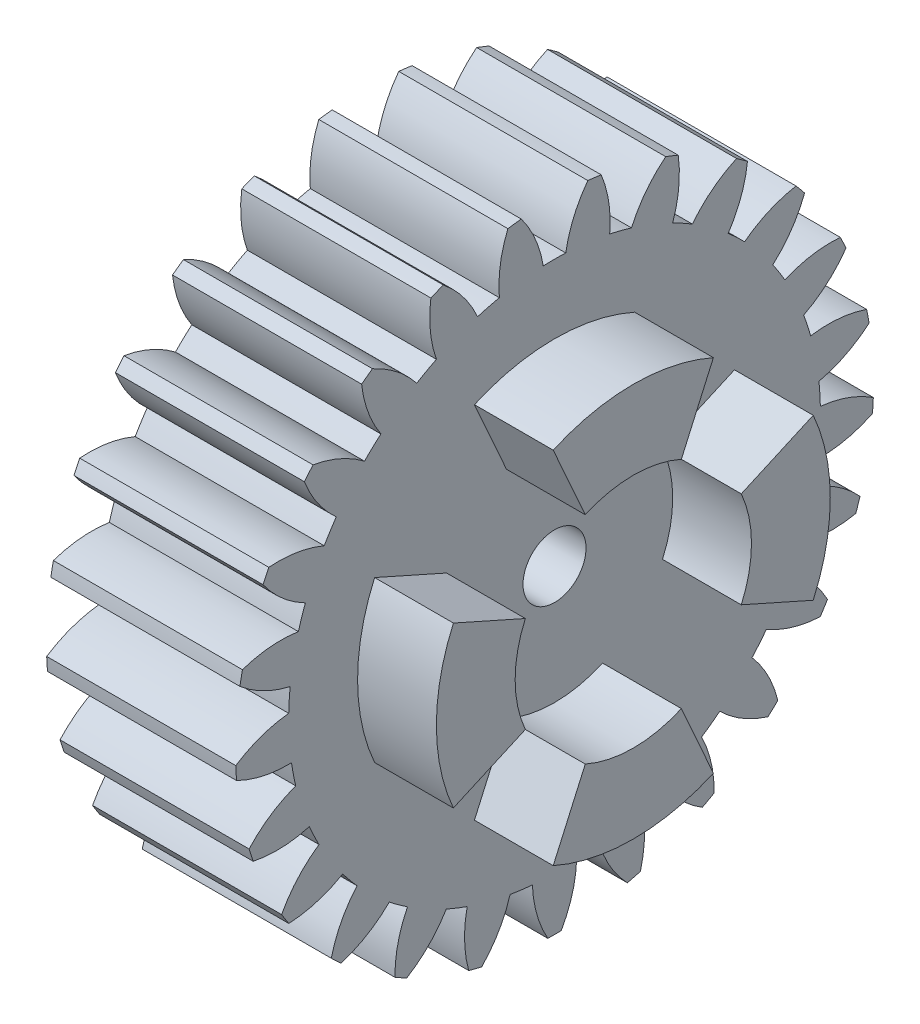
SolidWorks part; units mm, degrees
ref_plane "Plane1" through (0, 0, 0) normal (0, 0, 1) x (1, 0, 0)
ref_plane "Plane2" through (0, 0, 0) normal (0, 1, 0) x (1, 0, 0)
ref_plane "Plane3" through (0, 0, 0) normal (1, 0, 0) x (0, 0, -1)
sketch "HoldingSke" plane through (0, 0, 0) normal (0, 1, 0) x (1, 0, 0)
  line L0 (0, 0) -> (0.6042, -0.2817)
  line L1 (-15, 0) -> (100, 0) construction
  line L2 (0, 0) -> (-2.1039, 2.3779)
  line L3 (0, 0) -> (-11.863, 4.5341)
  line L4 (0, 0) -> (7.8269, 3.6497)
  line L5 (0, 0) -> (-46.8476, -17.4728)
  line L6 (0, 0) -> (-9.9476, -6.7116)
  line L7 (-2.1039, 2.3779) -> (8.6586, 51.2059)
  line L8 (-76.2, 54.61) -> (-75.5, 54.61)
  line L9 (-71.009, 38.7566) -> (-53.1078, 45.2721)
  line L10 (-76.2, 71.12) -> (104.1128, 71.12)
  line L11 (0, 0) -> (-12, 0)
  line L12 (-76.2, 101.6) -> (-76.147, 101.6)
  line L13 (24.9733, 27.94) -> (52.9518, 28.4284)
  line L14 (24.9733, 27.94) -> (24.9743, 27.94)
  line L15 (24.9733, 27.94) -> (100.4006, 29.5858)
  line L16 (-63.627, -1.5) -> (-12.827, -1.5)
  circle A0 centre (0, 0) radius 2
  circle A1 centre (0, 0) radius 16.874
  circle A2 centre (0, 0) radius 37.5
  circle A3 centre (0, 0) radius 2
  dimension "MHD" = 33.748
  dimension "Hub_dia" = 75
  dimension "Bore" = 4
  dimension "MBD" = 4
  dimension "Num_teeth" = 25
  dimension "Pitch" = 0.6667
  dimension "Overall_len" = 50
  dimension "Show_teeth" = 25
  dimension "Thickness" = 12
  dimension "OAL" = 50.0001
  dimension "T_dim" = 0.7
  dimension "Ap" = 20
  dimension "H" = 19.05
  dimension "Pitch_radius" = 180.3128
  dimension "Width" = 12
  dimension "Backlash" = 0.053
  dimension "Addendum_fac" = 1
  dimension "Dedendum_fac" = 1.25
  dimension "Clearance_fac" = 0.25
  dimension "Dedendum_add" = 0.001
  dimension "Module" = 1.5
sketch "BasProSke" plane through (0, 0, 0) normal (0, 1, 0) x (1, 0, 0)
  line L0 (-10, 0) -> (60, 0) construction
  line L1 (0, 0) -> (0, 20.25)
  line L2 (0, 0) -> (12, 0)
  line L3 (12, 0) -> (12, 20.25)
  line L4 (12, 20.25) -> (0, 20.25)
  dimension "Thickness" = 12
  dimension "Diameter" = 40.5
revolve "Base-Revolve" add sketch "BasProSke" angle 360 about L0
sketch "TooCutSke" plane through (0, 0, 0) normal (1, 0, 0) x (0, 0, -1)
  line L1 (0, 0) -> (0, 107) construction
  line L2 (0, 0) -> (-1.27, 18.7069) construction
  line L3 (0, 0) -> (-4.6921, 37.142) construction
  line L4 (-1.27, 18.7069) -> (-2.3461, 18.571) construction
  arc A0 (0.7139, 16.8589) -> (-0.7139, 16.8589) centre (0, 0) ccw
  arc A1 (2.1318, 20.163) -> (-2.1318, 20.163) centre (0, 0) ccw
  circle A2 centre (0, 0) radius 18.75 construction
  circle A3 centre (0, 0) radius 17.6192 construction
  arc A4 (-0.7139, 16.8589) -> (-2.1318, 20.163) centre (-8.1141, 15.6396) ccw
  arc A5 (2.1318, 20.163) -> (0.7139, 16.8589) centre (8.1141, 15.6396) ccw
  dimension "Root_dia" = 33.748
  dimension "Overcut_dia" = 40.5508
  dimension "Pitch_dia" = 37.5
  dimension "Base_dia" = 35.2385
  dimension "Flank_rad" = 7.5
  dimension "Half_ang" = 7.2
  dimension "Half_CT" = 1.0846
extrude "ToothCut" cut sketch "TooCutSke" along normal through all
fillet "Breaks" [suppressed] radius 0.03
fillet "RootFillets" [suppressed] radius 0.376
pattern_circular "TeethCuts" count 25 every 14.4 about axis through (-10, 0, 0) along (1, 0, 0) of "ToothCut", "RootFillets", "Breaks"
sketch "HubNeaOneSke" plane through (0, 0, 0) normal (-1, 0, 0) x (0, 0, 1)
  circle A0 centre (0, 0) radius 16.874
  dimension "Diameter" = 33.748
extrude "HubNearOne" [suppressed] add sketch "HubNeaOneSke" along normal blind 38.0001
sketch "HubNeaBotSke" plane through (0, 0, 0) normal (-1, 0, 0) x (0, 0, 1)
  circle A0 centre (0, 0) radius 16.874
  dimension "Diameter" = 33.748
extrude "HubNearBoth" [suppressed] add sketch "HubNeaBotSke" along normal blind 19
ref_plane "FarPln" through (12, 0, 0) normal (1, 0, 0) x (0, 0, -1)
sketch "HubFarSke" plane through (12, 0, 0) normal (1, 0, 0) x (0, 0, -1)
  circle A0 centre (0, 0) radius 16.874
  dimension "Diameter" = 33.748
extrude "HubFar" [suppressed] add sketch "HubFarSke" along normal blind 19
sketch "BorSke" plane through (0, 0, 0) normal (1, 0, 0) x (0, 0, -1)
  circle A0 centre (0, 0) radius 2
  dimension "Diameter" = 4
extrude "Bore" cut sketch "BorSke" along normal mid plane 100.0001
sketch "KeySke" plane through (0, 0, 0) normal (1, 0, 0) x (0, 0, -1)
  line L0 (-0.8, 0) -> (-0.8, 2.7)
  line L1 (-0.8, 2.7) -> (0.8, 2.7)
  line L2 (0.8, 2.7) -> (0.8, 0)
  line L3 (0, 0) -> (0, 34) construction
  line L4 (-0.8, 0) -> (0.8, 0)
  dimension "Offset" = 2.7
  dimension "Width" = 1.6
extrude "Keyway" [suppressed] cut sketch "KeySke" along normal mid plane 100.0001
pattern_circular "Keyway2" [suppressed] count 2 every 90 about axis through (-10, 0, 0) along (1, 0, 0)
sketch "草图2" plane through (12, 0, 0) normal (1, 0, 0) x (0, 0, -1)
  line L0 (-3.0499, 6.8519) -> (-5.0831, 11.4198)
  line L1 (0, 12.5) -> (0, 7.5) construction
  line L2 (3.0499, 6.8519) -> (5.0831, 11.4198)
  line L3 (0, -7.5) -> (0, -12.5) construction
  line L4 (0, 0) -> (0, -7.5) construction
  line L5 (6.8519, 3.0499) -> (11.4198, 5.0831)
  line L6 (6.8519, -3.0499) -> (11.4198, -5.0831)
  line L7 (3.0499, -6.8519) -> (5.0831, -11.4198)
  line L8 (-3.0499, -6.8519) -> (-5.0831, -11.4198)
  line L9 (-6.8519, -3.0499) -> (-11.4198, -5.0831)
  line L10 (-6.8519, 3.0499) -> (-11.4198, 5.0831)
  arc A0 (5.0831, 11.4198) -> (-5.0831, 11.4198) centre (0, 0) ccw
  arc A1 (3.0499, 6.8519) -> (-3.0499, 6.8519) centre (0, 0) ccw
  arc A2 (-5.0831, 11.4198) -> (0, -12.5) centre (0, 0) ccw construction
  arc A3 (-3.0499, 6.8519) -> (0, -7.5) centre (0, 0) ccw construction
  arc A4 (0, -7.5) -> (3.0499, 6.8519) centre (0, 0) ccw construction
  arc A5 (0, -12.5) -> (5.0831, 11.4198) centre (0, 0) ccw construction
  arc A6 (6.8519, -3.0499) -> (6.8519, 3.0499) centre (0, 0) ccw
  arc A7 (11.4198, -5.0831) -> (11.4198, 5.0831) centre (0, 0) ccw
  arc A8 (-3.0499, -6.8519) -> (3.0499, -6.8519) centre (0, 0) ccw
  arc A9 (-5.0831, -11.4198) -> (5.0831, -11.4198) centre (0, 0) ccw
  arc A10 (-6.8519, 3.0499) -> (-6.8519, -3.0499) centre (0, 0) ccw
  arc A11 (-11.4198, 5.0831) -> (-11.4198, -5.0831) centre (0, 0) ccw
  point P25 (0, 0)
  dimension "D1" = 25
  dimension "D2" = 15
  dimension "D3" = 4
extrude "凸台-拉伸1" add sketch "草图2" along normal blind 5
equation "' \"Module@HoldingSke\" = 6.35"
equation "' \"Num_teeth@HoldingSke\" = 12"
equation "' \"Ap@HoldingSke\" =  20"
equation "' \"Ap@HoldingSke\" = 20"
equation "' \"Width@HoldingSke\" = 0.5 * 25.4"
equation "' \"Hub_dia@HoldingSke\"= 1 * 25.4"
equation "' \"Hub_dia@HoldingSke\" = 1 * 25.4"
equation "' \"Overall_len@HoldingSke\" = 1.0 * 25.4"
equation "' \"Bore@HoldingSke\" = 0.75 * 25.4"
equation "' \"T_dim@HoldingSke\" = 0.1 * 25.4"
equation "' \"Width@KeySke\" = 0.25 * 25.4"
equation "' \"Show_teeth@HoldingSke\" = 13"
equation "' \"Backlash@HoldingSke\" = 0.009 * 25.4"
equation "' \"Addendum_fac@HoldingSke\" = 1.0"
equation "' \"Dedendum_fac@HoldingSke\" = 1.25"
equation "' \"Dedendum_add@HoldingSke\" = 0.00005 * 25.4"
equation "' \"Clearance_fac@HoldingSke\" = 0.25"
equation "\"Pitch@HoldingSke\" = 1 / \"Module@HoldingSke\""
equation "\"Overcut_dia@TooCutSke\" = (\"Num_teeth@HoldingSke\" + 2 * \"Addendum_fac@HoldingSke\") / \"Pitch@HoldingSke\" + 0.002 * 25.4"
equation "\"Pitch_dia@TooCutSke\" = \"Num_teeth@HoldingSke\" / \"Pitch@HoldingSke\""
equation "\"Base_dia@TooCutSke\" = \"Num_teeth@HoldingSke\" / \"Pitch@HoldingSke\" * cos((\"Ap@HoldingSke\"  * 3.14159265 / 180))"
equation "\"Root_dia@TooCutSke\" = (\"Num_teeth@HoldingSke\" + 2) / \"Pitch@HoldingSke\" - 2 * (\"Addendum_fac@HoldingSke\" + \"Dedendum_fac@HoldingSke\") / \"Pitch@HoldingSke\" - \"Dedendum_add@HoldingSke\" * 2"
equation "\"Half_ang@TooCutSke\" = 180 / \"Num_teeth@HoldingSke\""
equation "\"Half_CT@TooCutSke\" = \"Num_teeth@HoldingSke\" / \"Pitch@HoldingSke\" * sin((3.14159265 / 2 / \"Num_teeth@HoldingSke\")) / 2 - 7 * \"Backlash@HoldingSke\" / 4"
equation "\"Flank_rad@TooCutSke\" = \"Num_teeth@HoldingSke\" / \"Pitch@HoldingSke\" / 5"
equation "\"Radius@RootFillets\" = \"Clearance_fac@HoldingSke\" / \"Pitch@HoldingSke\" + \"Dedendum_add@HoldingSke\""
equation "\"Break_rad@Breaks\" = 0.02 / \"Pitch@HoldingSke\""
equation "\"Thickness@HoldingSke\" = \"Width@HoldingSke\""
equation "\"OAL@HoldingSke\" = \"Thickness@HoldingSke\""
equation "\"MHD@HoldingSke\" = (\"Num_teeth@HoldingSke\" + 2) / \"Pitch@HoldingSke\" - 2 * (\"Addendum_fac@HoldingSke\" + \"Dedendum_fac@HoldingSke\")  / \"Pitch@HoldingSke\" - \"Dedendum_add@HoldingSke\" * 2"
equation "\"MBD@HoldingSke\" = (\"Num_teeth@HoldingSke\" + 2) / \"Pitch@HoldingSke\" - 2 * (\"Addendum_fac@HoldingSke\" + \"Dedendum_fac@HoldingSke\")  / \"Pitch@HoldingSke\" - \"Dedendum_add@HoldingSke\" * 2 - 0.002 * 25.4"
equation "\"MHD@HoldingSke\" = ((sgn( \"MHD@HoldingSke\" - \"Hub_dia@HoldingSke\" )-1)*( \"MHD@HoldingSke\" - \"Hub_dia@HoldingSke\" ))/-2+ \"Hub_dia@HoldingSke\""
equation "\"MBD@HoldingSke\" = ((sgn( \"MBD@HoldingSke\" - \"Bore@HoldingSke\" )-1)*( \"MBD@HoldingSke\" - \"Bore@HoldingSke\" ))/-2+ \"Bore@HoldingSke\""
equation "\"OAL@HoldingSke\" = ((sgn( \"OAL@HoldingSke\" - \"Overall_len@HoldingSke\" )+1)*( \"OAL@HoldingSke\" - \"Overall_len@HoldingSke\" ))/2 + \"Overall_len@HoldingSke\" + 0.000002 * 25.4"
equation "\"Num_teeth@TeethCuts\" = int( \"Show_teeth@HoldingSke\" ) + 1"
equation "\"Num_teeth@TeethCuts\" = ((sgn( \"Num_teeth@TeethCuts\" - \"Num_teeth@HoldingSke\" )-1)*( \"Num_teeth@TeethCuts\" - \"Num_teeth@HoldingSke\" ))/-2+ \"Num_teeth@HoldingSke\""
equation "\"Num_teeth@TeethCuts\" = ((sgn( \"Num_teeth@TeethCuts\" - 2.0)+1)*( \"Num_teeth@TeethCuts\" - 2.0))/2 +2.0"
equation "\"Angle@TeethCuts\" = 360.0 / \"Num_teeth@HoldingSke\""
equation "\"Diameter@BasProSke\" = (\"Num_teeth@HoldingSke\" + 2 * \"Addendum_fac@HoldingSke\") / \"Pitch@HoldingSke\""
equation "\"Thickness@BasProSke\"  = \"Thickness@HoldingSke\""
equation "' \"Fillet_rad@BasProSke\" =  \"Thickness@HoldingSke\" * 0.05"
equation "' \"Fillet_rad@BasProSke\" = \"Thickness@HoldingSke\" * 0.05"
equation "\"MHD@HoldingSke\" = ((sgn( \"MHD@HoldingSke\" - \"Root_dia@TooCutSke\" )-1)*( \"MHD@HoldingSke\" - \"Root_dia@TooCutSke\" ))/-2+ \"Root_dia@TooCutSke\""
equation "\"Diameter@HubNeaOneSke\" = \"MHD@HoldingSke\""
equation "\"Length@HubNearOne\" = \"OAL@HoldingSke\" - \"Thickness@BasProSke\""
equation "\"Diameter@HubNeaBotSke\" = \"MHD@HoldingSke\""
equation "\"Length@HubNearBoth\" = ( \"OAL@HoldingSke\" - \"Thickness@BasProSke\" ) / 2.0"
equation "\"Thickness@FarPln\" = \"Thickness@BasProSke\""
equation "\"Diameter@HubFarSke\" = \"MHD@HoldingSke\""
equation "\"Length@HubFar\" = ( \"OAL@HoldingSke\" - \"Thickness@BasProSke\" ) / 2.0"
equation "\"Diameter@BorSke\" = \"MBD@HoldingSke\""
equation "\"D1@Bore\" = \"OAL@HoldingSke\" * 2.0"
equation "\"D1@Keyway\" = \"OAL@HoldingSke\" * 2.0"
equation "\"Offset@KeySke\" = \"T_dim@HoldingSke\" + \"MBD@HoldingSke\" / 2.0"
